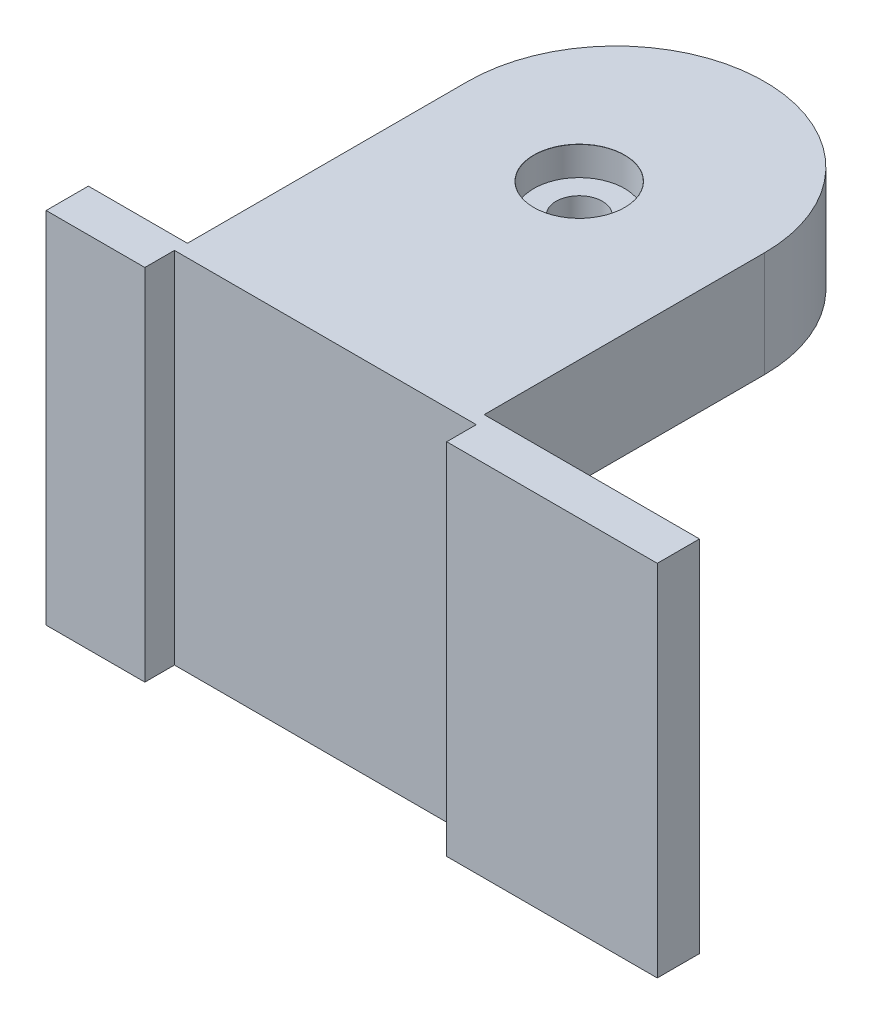
SolidWorks part; units mm, degrees
ref_plane "Plano frontal" through (0, 0, 0) normal (0, 0, 1) x (1, 0, 0)
ref_plane "Plano superior" through (0, 0, 0) normal (0, 1, 0) x (1, 0, 0)
ref_plane "Plano direito" through (0, 0, 0) normal (1, 0, 0) x (0, 0, -1)
sketch "Esboço2" plane through (0, 0, 0) normal (0, 0, 1) x (1, 0, 0)
  line L1 (55.0504, 42.6568) -> (-89.637, 42.6568)
  line L2 (55.0504, 42.6568) -> (55.0504, -42.3686)
  line L3 (55.0504, -42.3686) -> (-89.637, -42.3686)
  line L4 (-89.637, 42.6568) -> (-89.637, -42.3686)
  point P4 (0, 0)
  point P5 (0, 0)
extrude "Ressalto-extrusão2" add sketch "Esboço2" along normal mid plane 10 contours L2 L1 L4 L3
sketch "Esboço4" plane through (0, 42.6568, 0) normal (0, 1, 0) x (1, 0, 0)
  line L0 (-66.1891, 5) -> (-66.1891, 71.3575)
  line L1 (55.0504, 5) -> (-89.637, 5) construction
  line L2 (4.0756, 71.3575) -> (4.0756, 5)
  line L7 (55.0504, 5) -> (-89.637, 5)
  line L8 (-89.637, 5) -> (-89.637, -5)
  line L9 (-89.637, -5) -> (55.0504, -5)
  line L10 (55.0504, -5) -> (55.0504, 5)
  line L11 (4.0756, 5) -> (-66.1891, 5)
  arc A0 (-66.1891, 71.3575) -> (4.0756, 71.3575) centre (-31.0567, 71.3575) cw
  dimension "D1" = 0
extrude "Ressalto-extrusão7" add sketch "Esboço4" against normal blind 25
ref_plane "Plano2" through (-66.1891, 42.6568, -5) normal (0, 0, 1) x (1, 0, 0)
sketch "Esboço9" plane through (-66.1891, 42.6568, -5) normal (0, 0, 1) x (1, 0, 0)
sketch "Esboço10" plane through (0, 0, 5) normal (0, 0, 1) x (1, 0, 0)
sketch "Esboço11" plane through (0, 0, 5) normal (0, 0, 1) x (1, 0, 0)
hole_wizard "Rebaixo para parafuso de cabeça sextavada de M101" positions "Esboço12" profile "Esboço13" counterbore size "M10" standard "Ansi Metric" end condition through all
sketch "Esboço12" plane through (0, 42.6568, 0) normal (0, 1, 0) x (1, 0, 0)
  point P0 (-32.5233, 64.1004)
sketch "Esboço13" plane through (-32.5233, 42.6568, -64.1004) normal (1, 0, 0) x (0, 0, 1)
  line L0 (0, 0) -> (0, 85.0254)
  line L1 (0, 85.0254) -> (5.5, 85.0254)
  line L3 (5.5, 85.0254) -> (5.5, 6.85)
  line L4 (10.74, 6.85) -> (5.5, 6.85)
  line L5 (10.74, 6.85) -> (10.74, 0.025)
  line L6 (10.74, 0.025) -> (10.765, 0)
  line L7 (10.765, 0) -> (0, 0)
  line L8 (-10.74, 0.025) -> (-10.765, 0) construction
  line L11 (0, -6.35) -> (0, 107.95) construction
  dimension "Thru Hole Dia." = 11
  dimension "Thru Hole Depth" = 85.0254
  dimension "C'Bore Dia." = 21.48
  dimension "C'Bore Depth" = 6.85
  dimension "Near C'Sink Dia." = 21.53
  dimension "Near C'Sink Angle" = 90
sketch "Esboço16" plane through (0, 42.6568, 0) normal (0, 1, 0) x (1, 0, 0)
  line L0 (55.0504, -5) -> (-89.637, -5) construction
  line L1 (-66.2635, 2.009) -> (5.2002, 2.009)
  line L2 (-66.2635, 2.009) -> (-66.2635, -5)
  line L3 (-66.2635, -5) -> (5.2002, -5)
  line L4 (5.2002, 2.009) -> (5.2002, -5)
extrude "Corte-extrusão11" cut sketch "Esboço16" against normal through all both and the other way through all
